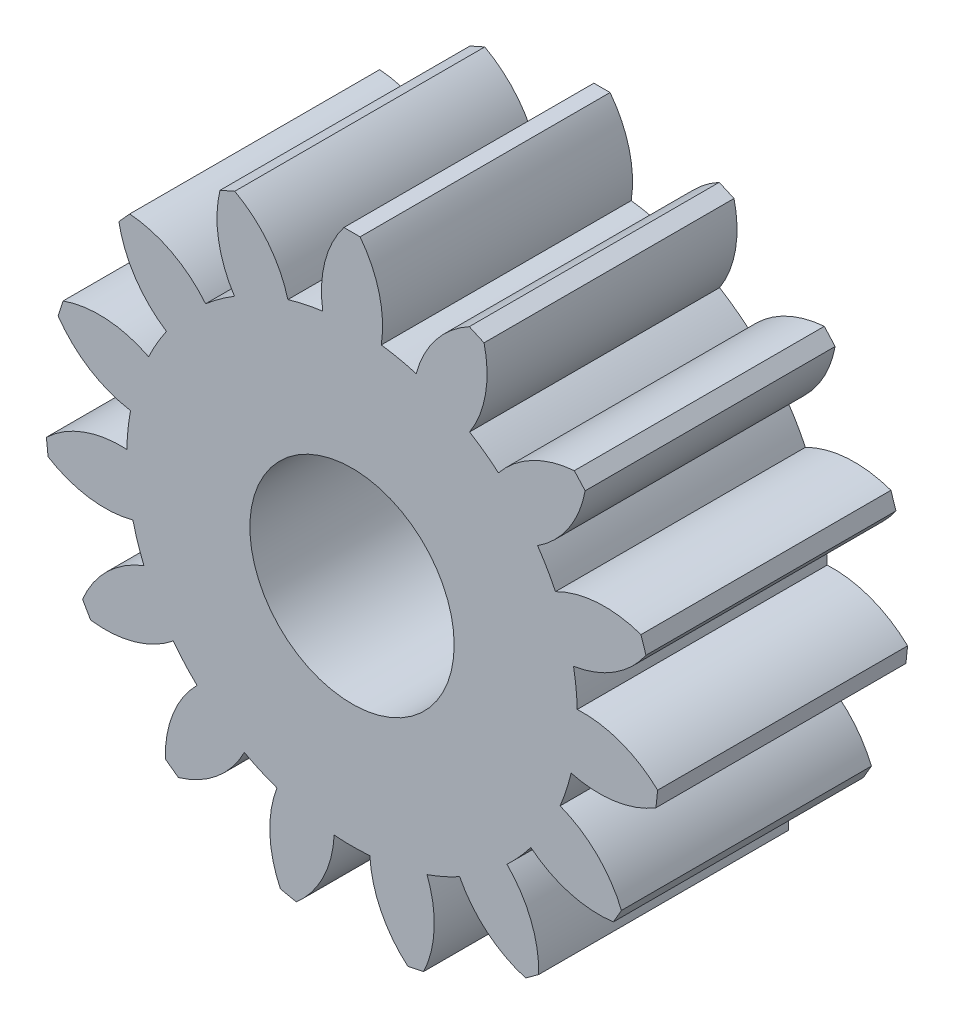
SolidWorks part; units mm, degrees
ref_plane "Plano frontal" through (0, 0, 0) normal (0, 0, 1) x (1, 0, 0)
ref_plane "Plano superior" through (0, 0, 0) normal (0, 1, 0) x (1, 0, 0)
ref_plane "Plano direito" through (0, 0, 0) normal (1, 0, 0) x (0, 0, -1)
sketch "Esboço1" plane through (0, 0, 0) normal (0, 0, 1) x (1, 0, 0)
  circle A0 centre (0, 0) radius 9.374
  dimension "D1" = 18.748
extrude "Ressalto-extrusão1" add sketch "Esboço1" along normal blind 10.4
sketch "Esboço2" plane through (0, 0, 10.4) normal (0, 0, 1) x (1, 0, 0)
  line L0 (0, 0) -> (0, 12.75) construction
  line L1 (-0.337, 12.75) -> (0.337, 12.75)
  line L2 (0, 0) -> (3.2505, 9.9968) construction
  arc A0 (-0.337, 12.75) -> (-1.2168, 9.2947) centre (3.2505, 9.9968) ccw
  arc A1 (1.2168, 9.2947) -> (-1.2168, 9.2947) centre (0, 0) ccw
  circle A2 centre (0, 0) radius 9.374 construction
  arc A3 (0.337, 12.75) -> (1.2168, 9.2947) centre (-3.2505, 9.9968) cw
  point P5 (0, 12.75)
  dimension "D1" = 12.75
  dimension "D2" = 0.674
  dimension "D3" = 18.012
  dimension "D4" = 10.512
extrude "Ressalto-extrusão2" add sketch "Esboço2" against normal blind 10.4
pattern_circular "PadrãoCircular1" count 15 over 360 about axis through (0, 0, 0) along (0, 0, 1) of "Ressalto-extrusão2"
sketch "Esboço4" plane through (0, 0, 10.4) normal (0, 0, 1) x (1, 0, 0)
  circle A0 centre (0, 0) radius 4.25
  dimension "D1" = 8.5
extrude "Corte-extrusão1" cut sketch "Esboço4" against normal blind 10.4
